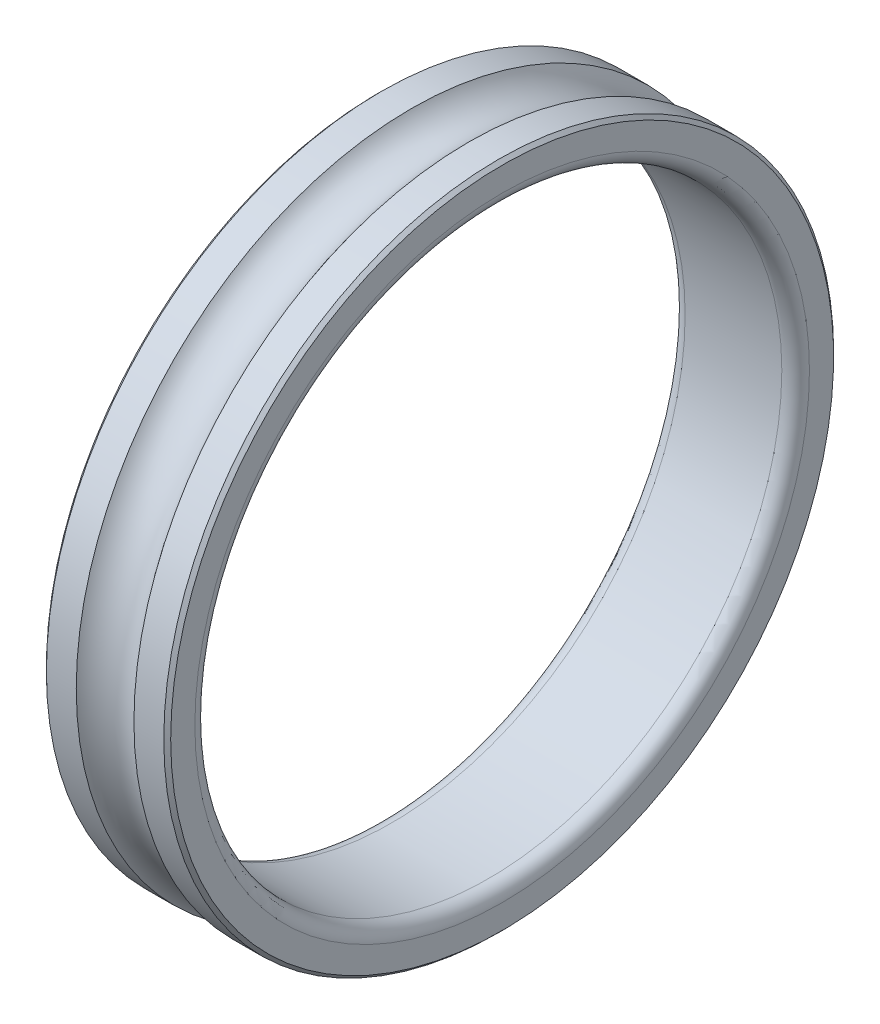
SolidWorks part; units mm, degrees
ref_plane "Plan1" through (0, 0, 0) normal (0, 0, 1) x (1, 0, 0)
ref_plane "Plan2" through (0, 0, 0) normal (0, 1, 0) x (1, 0, 0)
ref_plane "Plan3" through (0, 0, 0) normal (1, 0, 0) x (0, 0, -1)
sketch "Esquisse1" plane through (0, 0, 0) normal (0, 0, 1) x (1, 0, 0)
  line L0 (2, 42.5) -> (16, 42.5)
  line L1 (0, 44.5) -> (0, 48.5)
  line L2 (0, 48.5) -> (4.8242, 48.5)
  line L3 (18, 48.5) -> (18, 44.5)
  line L4 (0, 0) -> (24.5928, 0) construction
  line L5 (13.1758, 48.5) -> (18, 48.5)
  line L6 (-69.8184, 0) -> (67.6701, 0) construction
  arc A0 (4.8242, 48.5) -> (13.1758, 48.5) centre (9, 51.25) ccw
  arc A1 (2, 42.5) -> (0, 44.5) centre (2, 44.5) cw
  arc A2 (18, 44.5) -> (16, 42.5) centre (16, 44.5) cw
  dimension "D1" = 42.5
  dimension "D6" = 5
  dimension "D7" = 2
  dimension "D2" = 48.5
  dimension "D3" = 51.25
  dimension "D4" = 18
  dimension "D5" = 9
revolve "Base-Révolution" add sketch "Esquisse1" angle 360 about L4
chamfer "Chanfrein2" distance 0.5 angle 45
